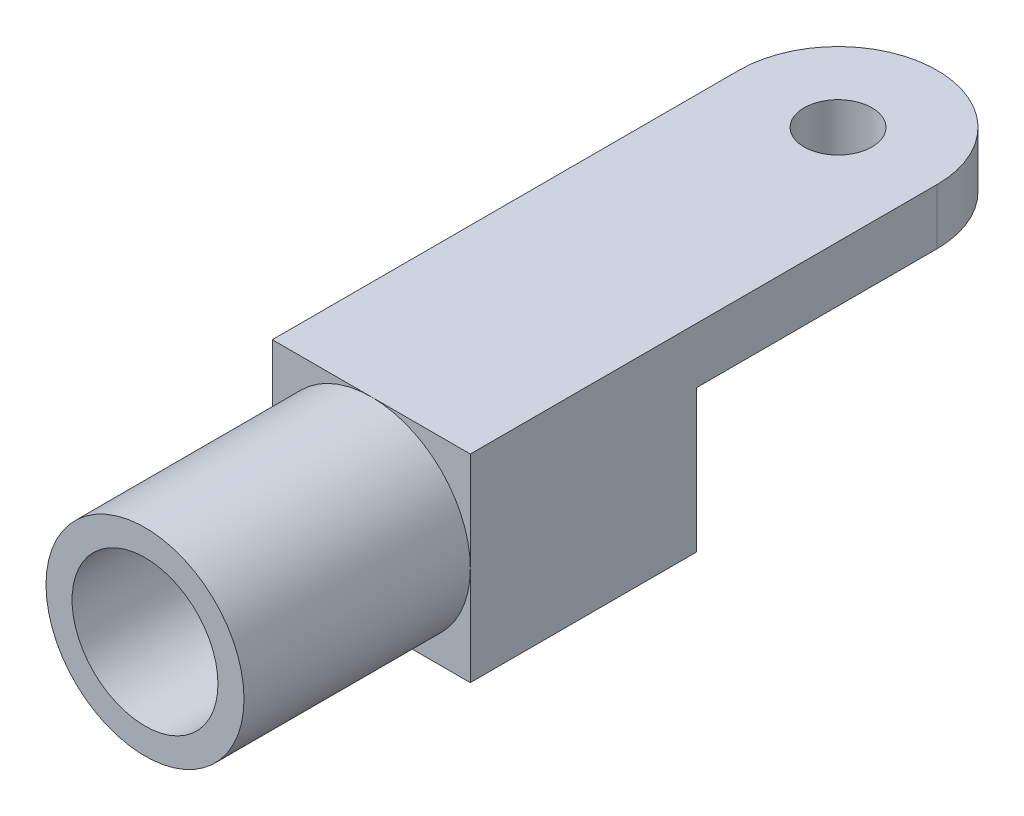
SolidWorks part; units mm, degrees
ref_plane "Front Plane" through (0, 0, 0) normal (0, 0, 1) x (1, 0, 0)
ref_plane "Top Plane" through (0, 0, 0) normal (0, 1, 0) x (1, 0, 0)
ref_plane "Right Plane" through (0, 0, 0) normal (1, 0, 0) x (0, 0, -1)
sketch "Sketch1" plane through (0, 0, 0) normal (0, 0, 1) x (1, 0, 0)
  circle A0 centre (0, 0) radius 3.275
  circle A1 centre (0, 0) radius 4.445
  dimension "D1" = 6.55
  dimension "D2" = 8.89
extrude "Boss-Extrude1" add sketch "Sketch1" along normal blind 10.16
sketch "Sketch2" plane through (0, 0, 0) normal (0, 0, -1) x (-1, 0, 0)
  line L1 (-4.445, 4.445) -> (4.445, 4.445)
  line L2 (-4.445, 4.445) -> (-4.445, -4.445)
  line L3 (-4.445, -4.445) -> (4.445, -4.445)
  line L4 (4.445, 4.445) -> (4.445, -4.445)
  circle A1 centre (0, 0) radius 4.445 construction
extrude "Boss-Extrude2" add sketch "Sketch2" along normal blind 25.4
sketch "Sketch3" plane through (0, -4.445, 0) normal (0, -1, 0) x (1, 0, 0)
  line L0 (4.445, -25.4) -> (-4.445, -25.4) construction
  line L1 (4.445, -25.4) -> (4.445, 0) construction
  line L2 (-4.445, -25.4) -> (-4.445, 0) construction
  line L3 (-4.445, -20.955) -> (-4.445, -25.4)
  line L4 (-4.445, -25.4) -> (4.445, -25.4)
  line L5 (4.445, -25.4) -> (4.445, -20.955)
  line L6 (4.445, -20.955) -> (-4.445, -20.955)
  circle A0 centre (0, -20.955) radius 4.445
  circle A1 centre (0, -20.955) radius 1.524
  line M3 (-4.445, 0) -> (-4.445, -25.4)
  line M4 (-4.445, -25.4) -> (4.445, -25.4)
  line M5 (4.445, -25.4) -> (4.445, 0)
  dimension "D1" = 3.048
extrude "Cut-Extrude1" cut sketch "Sketch3" against normal through all contours A0 L4 M5 | A0 M3 M4 | L6 A1 | L6 A1
sketch "Sketch4" plane through (-4.445, 0, 0) normal (-1, 0, 0) x (0, 0, 1)
  line L0 (-20.955, -4.445) -> (0, -4.445) construction
  line L1 (-10.16, -4.445) -> (-25.4, -4.445)
  line L2 (-10.16, -4.445) -> (-10.16, 1.9456)
  line L3 (-10.16, 1.9456) -> (-25.4, 1.9456)
  line L4 (-25.4, -4.445) -> (-25.4, 1.9456)
  line L5 (-25.4, 4.445) -> (-25.4, -4.445) construction
  line L9 (-17.78, -4.445) -> (-17.78, 1.9456) construction
  dimension "D1" = 15.24
  dimension "D2" = 6.3906
extrude "Cut-Extrude2" cut sketch "Sketch4" against normal through all
